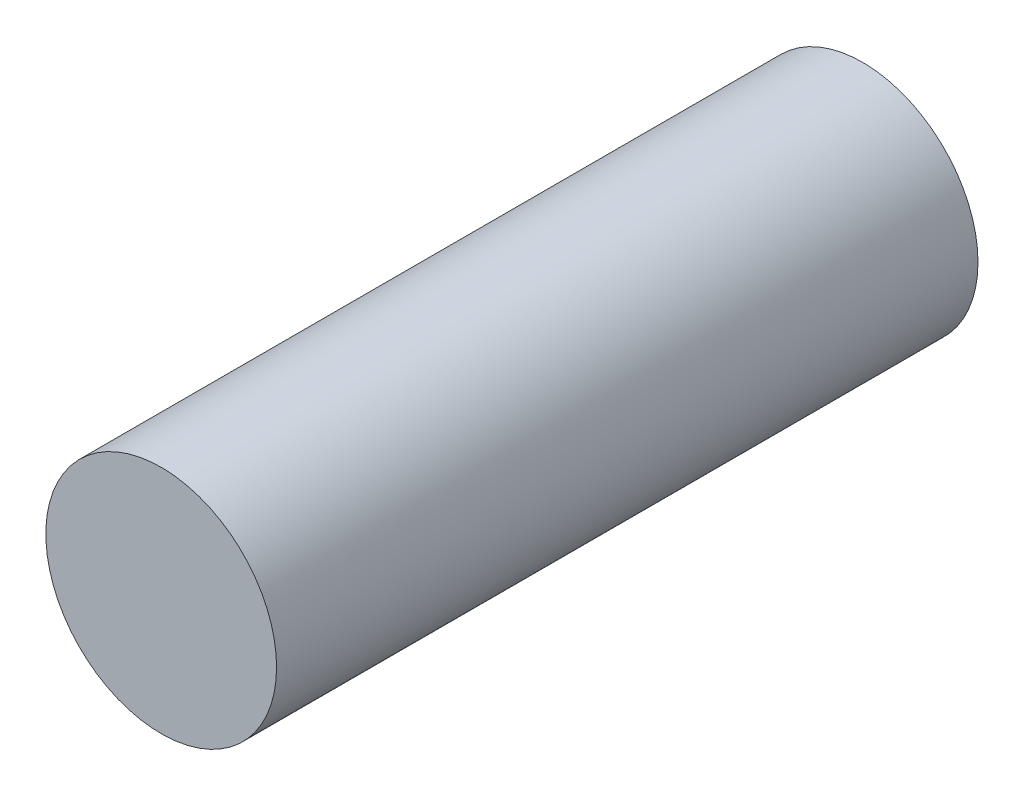
SolidWorks part; units mm, degrees
ref_plane "Front Plane" through (0, 0, 0) normal (0, 0, 1) x (1, 0, 0)
ref_plane "Top Plane" through (0, 0, 0) normal (0, 1, 0) x (1, 0, 0)
ref_plane "Right Plane" through (0, 0, 0) normal (1, 0, 0) x (0, 0, -1)
sketch "Sketch1" plane through (0, 0, 0) normal (0, 0, 1) x (1, 0, 0)
  circle A1 centre (-2.7044, 8.3864) radius 0.25
extrude "Boss-Extrude1" add sketch "Sketch1" along normal mid plane 1.52
